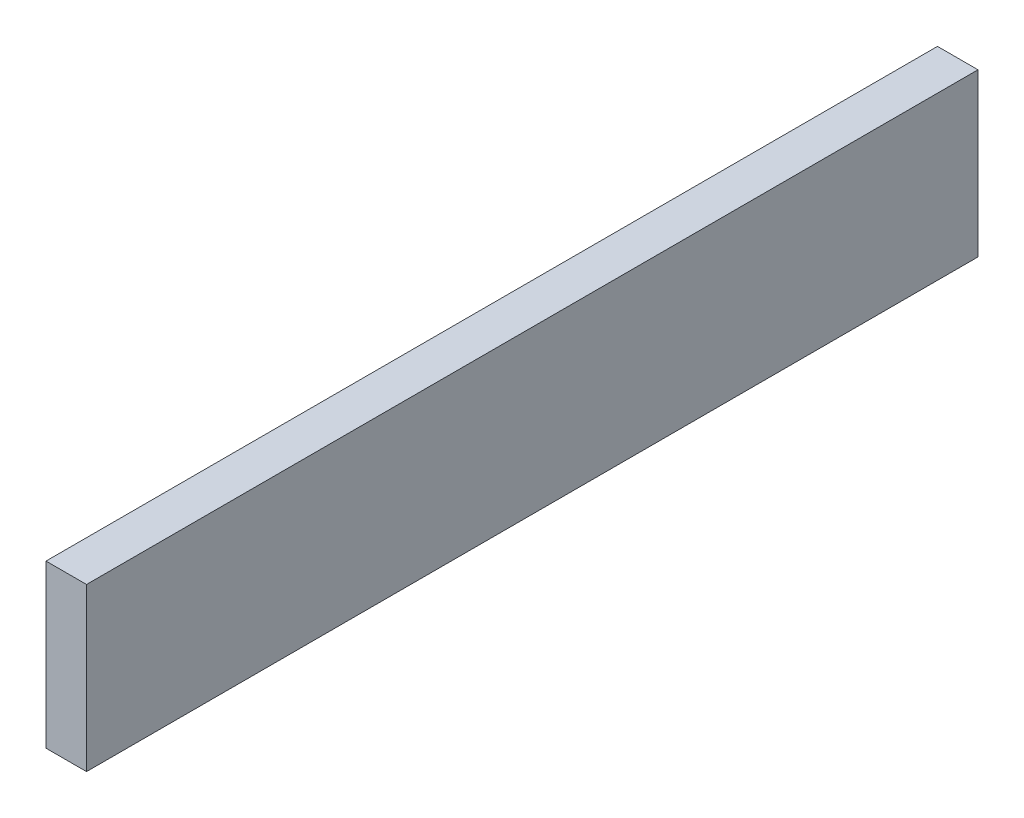
SolidWorks part; units mm, degrees
material "PE High Density"
ref_plane "Front Plane" through (0, 0, 0) normal (0, 0, 1) x (1, 0, 0)
ref_plane "Top Plane" through (0, 0, 0) normal (0, 1, 0) x (1, 0, 0)
ref_plane "Right Plane" through (0, 0, 0) normal (1, 0, 0) x (0, 0, -1)
sketch "Sketch1" plane through (0, 0, 0) normal (0, 0, 1) x (1, 0, 0)
  line L1 (0, 0) -> (6.35, 0)
  line L2 (0, 0) -> (0, 25.4)
  line L3 (0, 25.4) -> (6.35, 25.4)
  line L4 (6.35, 0) -> (6.35, 25.4)
  dimension "D1" = 25.4
  dimension "D2" = 6.35
extrude "Boss-Extrude1" add sketch "Sketch1" along normal blind 139.7
